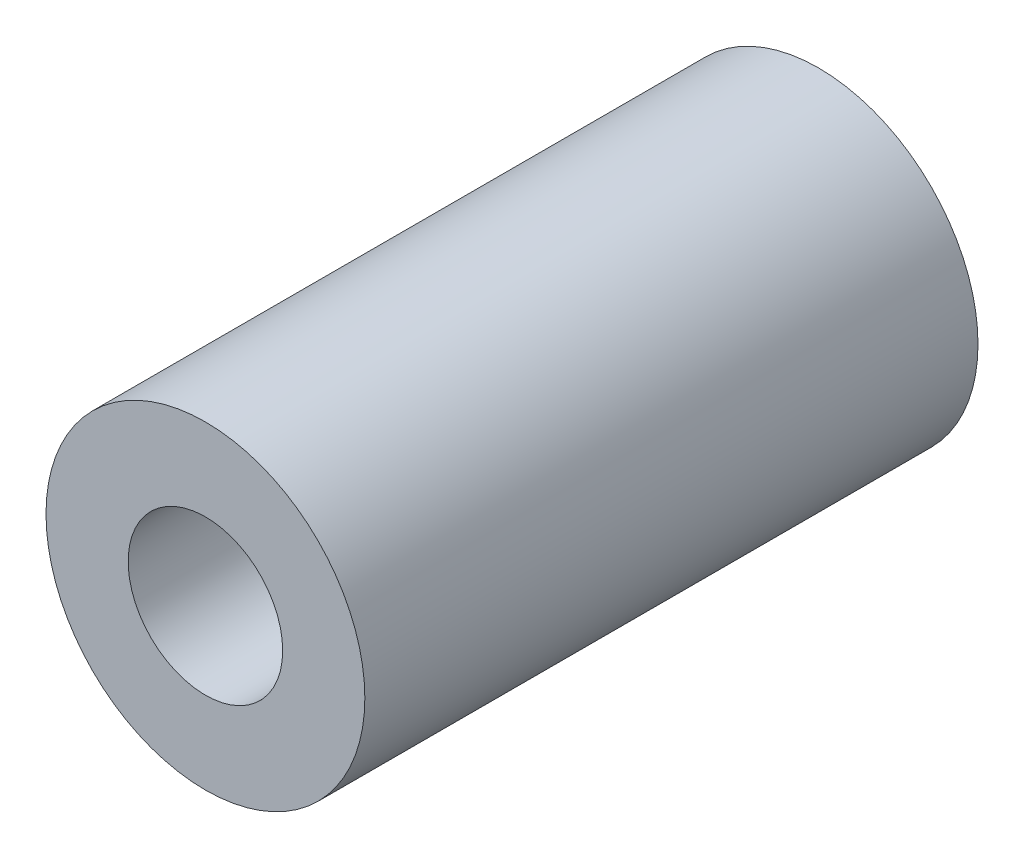
SolidWorks part; units mm, degrees
ref_plane "Front Plane" through (0, 0, 0) normal (0, 0, 1) x (1, 0, 0)
ref_plane "Top Plane" through (0, 0, 0) normal (0, 1, 0) x (1, 0, 0)
ref_plane "Right Plane" through (0, 0, 0) normal (1, 0, 0) x (0, 0, -1)
sketch "Sketch1" plane through (0, 0, 0) normal (0, 0, 1) x (1, 0, 0)
  line L0 (0, 3.15) -> (0, 6.5) construction
  line L1 (0, -3.15) -> (0, -6.5) construction
  circle A0 centre (0, 0) radius 6.5
  circle A1 centre (0, 0) radius 3.15
  dimension "OD" = 13
  dimension "ID" = 6.3
sketch "Sketch2" plane through (0, 0, 0) normal (1, 0, 0) x (0, 0, -1)
  line L0 (-12.5, 3.15) -> (12.5, 3.15) construction
  line L1 (-12.5, -3.15) -> (12.5, -3.15) construction
  line L2 (-12.5, -6.5) -> (12.5, -6.5) construction
  line L3 (-12.5, 6.5) -> (12.5, 6.5) construction
  dimension "Length" = 25
extrude "Extrude1" add sketch "Sketch1" along normal up to vertex (12.5 mm away) and the other way up to vertex (12.5 mm away) up to point (0, 3.15, 12.5) other way up to point (0, 3.15, -12.5)
sketch "Sketch3" plane through (0, 0, 12.5) normal (0, 0, 1) x (1, 0, 0)
  circle A0 centre (0, 0) radius 3.15 construction
  circle A3 centre (0, 0) radius 3.15
  point P3 (-3.15, 0)
